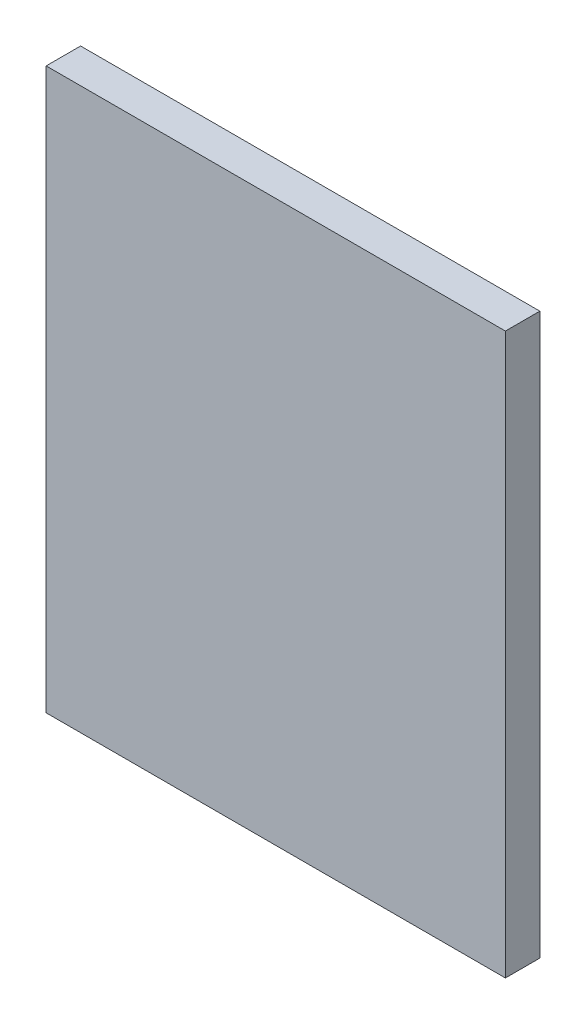
SolidWorks part; units mm, degrees
ref_plane "Alzado" through (0, 0, 0) normal (1, 0, 0) x (0, 1, 0)
ref_plane "Planta" through (0, 0, 0) normal (0, 0, 1) x (0, 1, 0)
ref_plane "Vista lateral" through (0, 0, 0) normal (0, 1, 0) x (-1, 0, 0)
sketch "Croquis2" plane through (0, 0, 0) normal (0, 0, 1) x (0, 1, 0)
  line L1 (0, 0) -> (244, 0)
  line L2 (0, 0) -> (0, 200)
  line L3 (0, 200) -> (244, 200)
  line L4 (244, 0) -> (244, 200)
  dimension "D1" = 244
  dimension "D2" = 200
extrude "Saliente-Extruir1" add sketch "Croquis2" along normal blind 15
